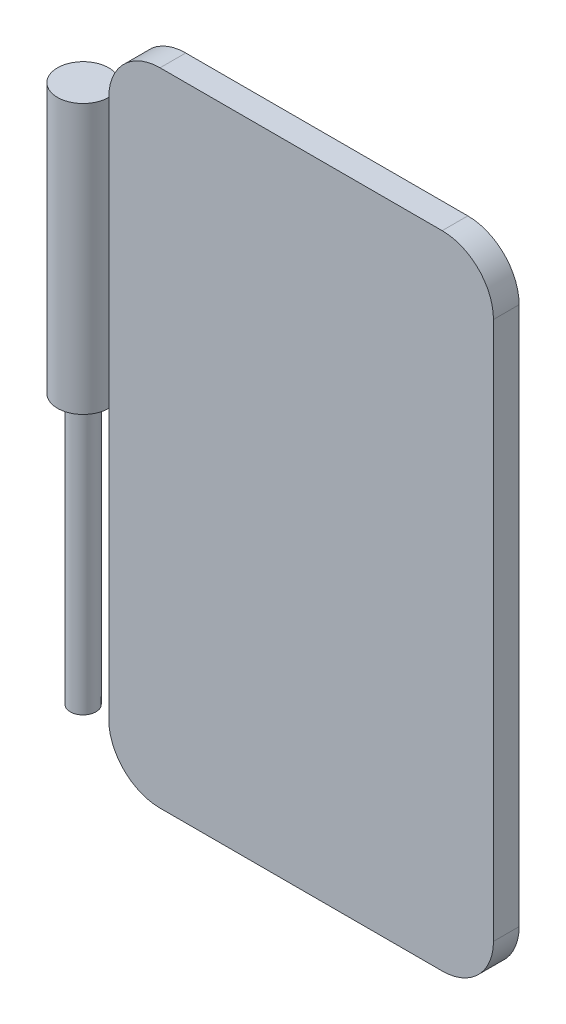
SolidWorks part; units mm, degrees
ref_plane "前视基准面" through (0, 0, 0) normal (0, 0, 1) x (1, 0, 0)
ref_plane "上视基准面" through (0, 0, 0) normal (0, 1, 0) x (1, 0, 0)
ref_plane "右视基准面" through (0, 0, 0) normal (1, 0, 0) x (0, 0, -1)
other "Configuration Table"
sketch "草图1" plane through (0, 0, 0) normal (0, 0, 1) x (1, 0, 0)
  line L1 (17.75, -8.875) -> (6.75, -8.875)
  line L2 (19.75, -6.875) -> (19.75, 14.125)
  line L3 (17.75, 16.125) -> (6.75, 16.125)
  line L4 (4.75, -6.875) -> (4.75, 14.125)
  line L5 (19.75, -8.875) -> (4.75, 16.125) construction
  line L6 (19.75, 16.125) -> (4.75, -8.875) construction
  arc A0 (4.75, -6.875) -> (6.75, -8.875) centre (6.75, -6.875) ccw
  arc A1 (17.75, -8.875) -> (19.75, -6.875) centre (17.75, -6.875) ccw
  arc A2 (19.75, 14.125) -> (17.75, 16.125) centre (17.75, 14.125) ccw
  arc A3 (4.75, 14.125) -> (6.75, 16.125) centre (6.75, 14.125) cw
  point P0 (12.25, 3.625)
  dimension "D3" = 2
  dimension "D1" = 15
  dimension "D2" = 25
extrude "凸台-拉伸1" add sketch "草图1" along normal mid plane 1
sketch "草图2" plane through (0, 0, 0.5) normal (0, 0, 1) x (1, 0, 0)
  line L0 (17.75, 16.125) -> (6.75, 16.125) construction
  line L1 (3.75, 14.125) -> (4.75, 14.125)
  line L2 (3.75, 14.125) -> (3.75, 3.625)
  line L3 (3.75, 3.625) -> (4.75, 3.625)
  line L4 (4.75, 14.125) -> (4.75, 3.625)
  line L6 (4.75, 14.125) -> (4.75, -6.875) construction
  line L8 (3.75, 3.625) -> (4.25, 3.625)
  line L9 (3.75, 3.625) -> (3.75, -6.875)
  line L10 (3.75, -6.875) -> (4.25, -6.875)
  line L11 (4.25, 3.625) -> (4.25, -6.875)
  dimension "D1" = 10.5
  dimension "D2" = 1
  dimension "D3" = 2
  dimension "D4" = 10.5
  dimension "D5" = 0.5
revolve "旋转1" add sketch "草图2" angle 360 about L2
